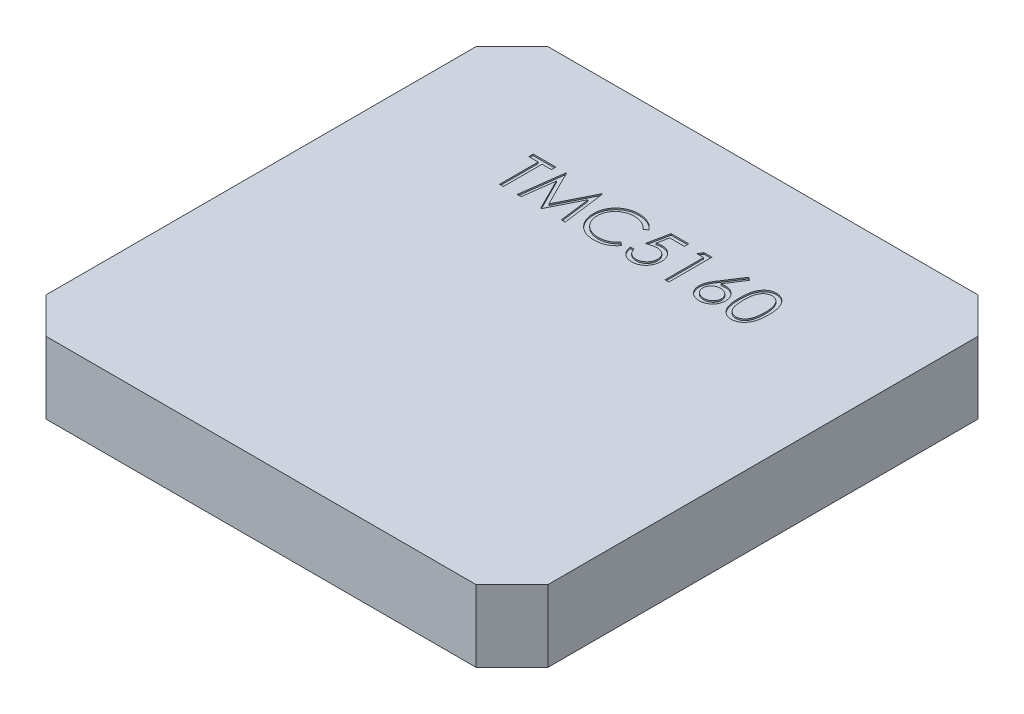
SolidWorks part; units mm, degrees
ref_plane "Front Plane" through (0, 0, 0) normal (0, 0, 1) x (1, 0, 0)
ref_plane "Top Plane" through (0, 0, 0) normal (0, 1, 0) x (1, 0, 0)
ref_plane "Right Plane" through (0, 0, 0) normal (1, 0, 0) x (0, 0, -1)
sketch "BaseS" plane through (0, 0, 0) normal (0, 1, 0) x (1, 0, 0)
  line L1 (-3.5, 3.5) -> (3.5, 3.5)
  line L2 (-3.5, 3.5) -> (-3.5, -3.5)
  line L3 (-3.5, -3.5) -> (3.5, -3.5)
  line L4 (3.5, 3.5) -> (3.5, -3.5)
  line L5 (-3.5, 3.5) -> (3.5, -3.5) construction
  line L6 (-3.5, -3.5) -> (3.5, 3.5) construction
  point P0 (0, 0)
  dimension "Dim" = 7
extrude "Base" add sketch "BaseS" along normal blind 1
sketch "PartNumberS" plane through (0, 1, 0) normal (0, 1, 0) x (1, 0, 0)
  line L0 (3.5, 1.5) -> (-3.5, 1.5) construction
  line L1 (3.5, -3.5) -> (3.5, 3.5) construction
  line L2 (-3.5, 3.5) -> (-3.5, -3.5) construction
  line L3 (-3.5, -3.5) -> (3.5, -3.5) construction
  text T0 "TMC5160\r\n" font "Century Gothic" height 0.6
  dimension "YDim" = 5
extrude "PartNumber" cut sketch "PartNumberS" against normal blind 0.02
chamfer "PNC" distance 0.5 angle 45 4 edges at (-3.5, 0.5, 3.5) (3.5, 0.5, 3.5) (3.5, 0.5, -3.5) (-3.5, 0.5, -3.5)
